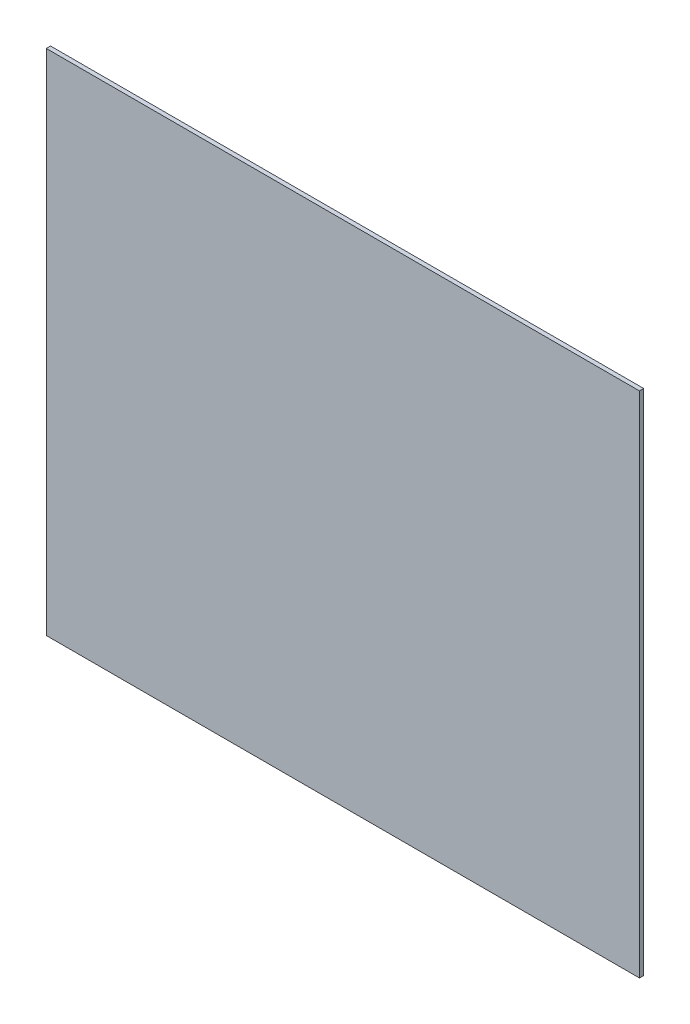
SolidWorks part; units mm, degrees
material "3003 Alloy"
ref_plane "Front Plane" through (0, 0, 0) normal (0, 0, 1) x (1, 0, 0)
ref_plane "Top Plane" through (0, 0, 0) normal (0, 1, 0) x (1, 0, 0)
ref_plane "Right Plane" through (0, 0, 0) normal (1, 0, 0) x (0, 0, -1)
sketch "Sketch1" plane through (0, 0, 0) normal (0, 0, 1) x (1, 0, 0)
  line L1 (140, -120) -> (-140, -120)
  line L2 (140, -120) -> (140, 120)
  line L3 (140, 120) -> (-140, 120)
  line L4 (-140, -120) -> (-140, 120)
  line L5 (140, -120) -> (-140, 120) construction
  line L6 (140, 120) -> (-140, -120) construction
  point P0 (0, 0)
  dimension "D1" = 240
  dimension "D2" = 280
extrude "Boss-Extrude1" add sketch "Sketch1" along normal blind 2
